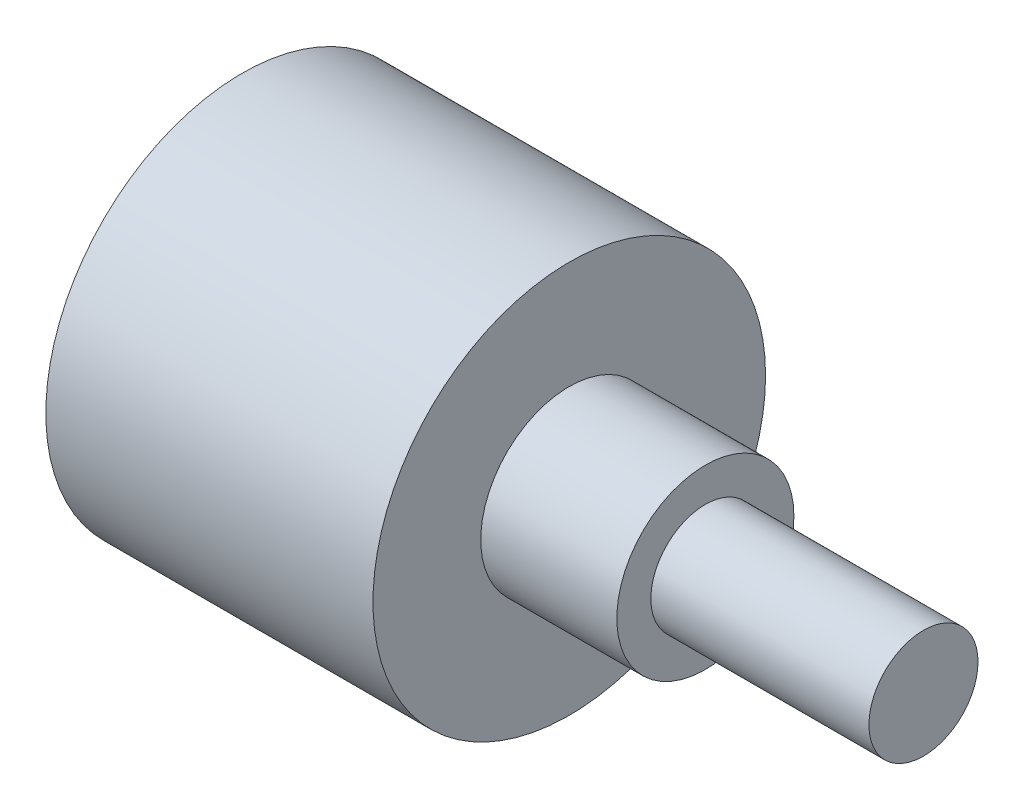
SolidWorks part; units mm, degrees
ref_plane "Front Plane" through (0, 0, 0) normal (0, 0, 1) x (1, 0, 0)
ref_plane "Top Plane" through (0, 0, 0) normal (0, 1, 0) x (1, 0, 0)
ref_plane "Right Plane" through (0, 0, 0) normal (1, 0, 0) x (0, 0, -1)
sketch "Sketch1" plane through (0, 0, 0) normal (0, 1, 0) x (1, 0, 0)
  line L0 (0, 0) -> (0, 11.43)
  line L1 (0, 11.43) -> (19.05, 11.43)
  line L2 (19.05, 11.43) -> (19.05, 5.1562)
  line L3 (19.05, 5.1562) -> (26.9748, 5.1562)
  line L4 (26.9748, 5.1562) -> (26.9748, 3.175)
  line L5 (26.9748, 3.175) -> (39.6748, 3.175)
  line L6 (39.6748, 3.175) -> (39.6748, 0)
  line L7 (39.6748, 0) -> (0, 0)
  line L8 (0, 0) -> (-5.5563, 0) construction
  dimension "D1" = 22.86
  dimension "D2" = 19.05
  dimension "D3" = 10.3124
  dimension "D4" = 6.35
  dimension "D5" = 7.9248
  dimension "D6" = 20.6248
revolve "Revolve1" add sketch "Sketch1" angle 360 about L8
